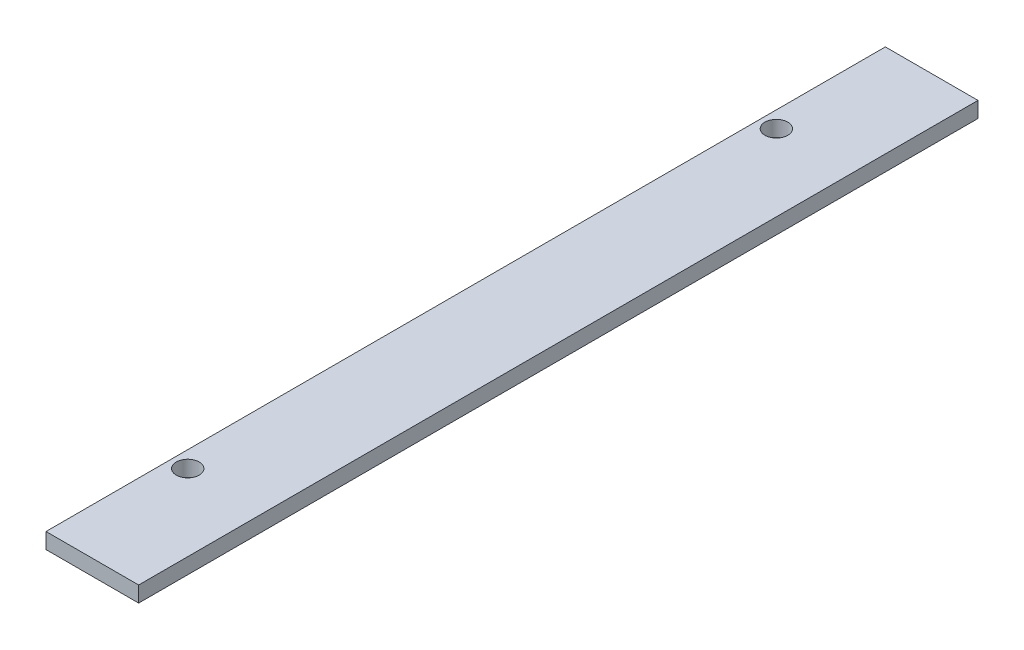
SolidWorks part; units mm, degrees
ref_plane "前视基准面" through (0, 0, 0) normal (0, 0, 1) x (1, 0, 0)
ref_plane "上视基准面" through (0, 0, 0) normal (0, 1, 0) x (1, 0, 0)
ref_plane "右视基准面" through (0, 0, 0) normal (1, 0, 0) x (0, 0, -1)
sketch "草图1" plane through (0, 0, 0) normal (0, 1, 0) x (1, 0, 0)
  line L1 (0, 0) -> (8.5, 0)
  line L2 (0, 0) -> (0, -77)
  line L3 (0, -77) -> (8.5, -77)
  line L4 (8.5, 0) -> (8.5, -77)
  dimension "D1" = 8.5
  dimension "D2" = 77
extrude "凸台-拉伸1" add sketch "草图1" along normal blind 1.44
sketch "草图2" plane through (0, 1.44, 0) normal (0, 1, 0) x (1, 0, 0)
  line L0 (0, 0) -> (0, -77) construction
  line L1 (0, -77) -> (8.5, -77) construction
  line L2 (8.5, 0) -> (0, 0) construction
  circle A0 centre (1.5, -65.5) radius 1.05
  circle A1 centre (1.5, -11.5) radius 1.05
  point P8 (1.5, -50.6947)
  dimension "D1" = 2.1
  dimension "D2" = 1.5
  dimension "D3" = 11.5
  dimension "D4" = 11.5
extrude "切除-拉伸1" cut sketch "草图2" against normal blind 1.44
